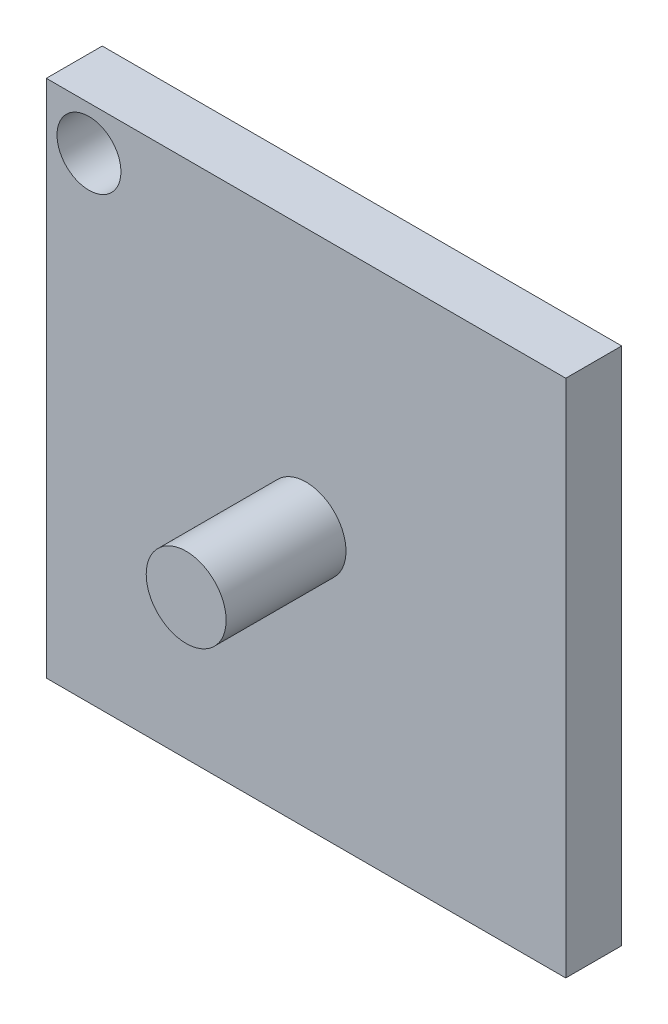
SolidWorks part; units mm, degrees
material "Natural Rubber"
ref_plane "Front Plane" through (0, 0, 0) normal (0, 0, 1) x (1, 0, 0)
ref_plane "Top Plane" through (0, 0, 0) normal (0, 1, 0) x (1, 0, 0)
ref_plane "Right Plane" through (0, 0, 0) normal (1, 0, 0) x (0, 0, -1)
sketch "Sketch2" plane through (0, 0, 0) normal (0, 0, 1) x (1, 0, 0)
  line L1 (-32.5, -32.5) -> (32.5, -32.5)
  line L2 (-32.5, -32.5) -> (-32.5, 32.5)
  line L3 (-32.5, 32.5) -> (32.5, 32.5)
  line L4 (32.5, -32.5) -> (32.5, 32.5)
  line L5 (-32.5, -32.5) -> (32.5, 32.5) construction
  line L6 (-32.5, 32.5) -> (32.5, -32.5) construction
  point P0 (0, 0)
  dimension "D1" = 65
  dimension "D2" = 65
extrude "Boss-Extrude1" add sketch "Sketch2" along normal blind 7
sketch "Sketch3" plane through (0, 0, 7) normal (0, 0, 1) x (1, 0, 0)
  circle A0 centre (0, 0) radius 5
  dimension "D1" = 10
extrude "Boss-Extrude2" add sketch "Sketch3" along normal blind 15
sketch "Sketch4" plane through (0, 0, 7) normal (0, 0, 1) x (1, 0, 0)
  circle A0 centre (-27.1624, 27.0376) radius 4
  dimension "D1" = 8
extrude "Cut-Extrude1" cut sketch "Sketch4" against normal through all
